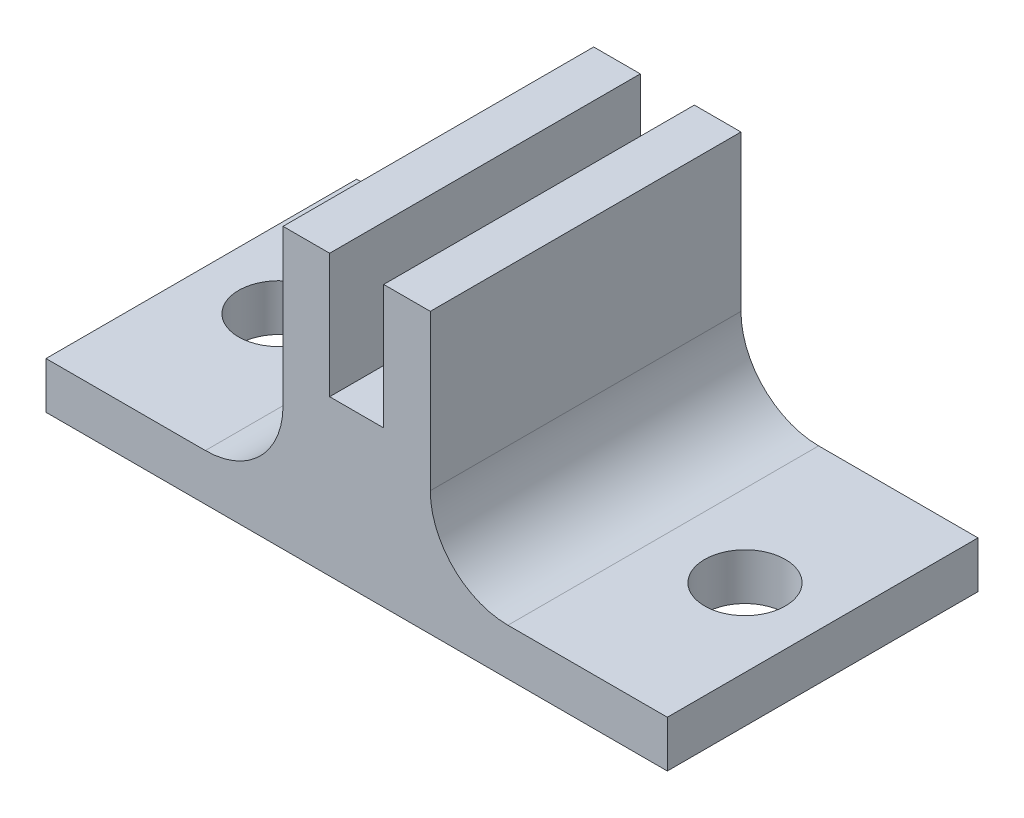
SolidWorks part; units mm, degrees
ref_plane "Front Plane" through (0, 0, 0) normal (0, 0, 1) x (1, 0, 0)
ref_plane "Top Plane" through (0, 0, 0) normal (0, 1, 0) x (1, 0, 0)
ref_plane "Right Plane" through (0, 0, 0) normal (1, 0, 0) x (0, 0, -1)
sketch "Sketch3" plane through (0, 0, 0) normal (0, 1, 0) x (1, 0, 0)
  line L0 (0, 0) -> (0, 20.1744) construction
  line L1 (-20, -10) -> (20, -10)
  line L2 (-20, -10) -> (-20, 10)
  line L3 (-20, 10) -> (20, 10)
  line L4 (20, -10) -> (20, 10)
  line L5 (-20, -10) -> (20, 10) construction
  line L6 (-20, 10) -> (20, -10) construction
  circle A0 centre (-15, 0) radius 2.6
  circle A1 centre (15, 0) radius 2.6
  point P0 (0, 0)
  dimension "D3" = 5.2
  dimension "D4" = 15
  dimension "D1" = 20
  dimension "D2" = 40
extrude "Jig base" add sketch "Sketch3" along normal blind 3
sketch "Sketch4" plane through (0, 3, 0) normal (0, 1, 0) x (1, 0, 0)
  line L5 (-4.74, 10) -> (-1.74, 10)
  line L6 (-1.74, 10) -> (1.74, 10) construction
  line L11 (-4.74, 10) -> (-4.74, -10)
  line L12 (-4.74, -10) -> (-1.74, -10)
  line L13 (-1.74, 10) -> (-1.74, -10)
  line L14 (4.74, -10) -> (1.74, -10)
  line L15 (4.74, -10) -> (4.74, 10)
  line L16 (4.74, 10) -> (1.74, 10)
  line L17 (1.74, -10) -> (1.74, 10)
  line L18 (20, 10) -> (-20, 10) construction
  point P12 (0, 10)
  point P18 (-1.74, 0)
  point P19 (1.74, 0)
  dimension "D1" = 3
  dimension "D2" = 3
  dimension "D3" = 3.48
  dimension "D4" = 20
extrude "jig wall" add sketch "Sketch4" along normal blind 15
sketch "Sketch5" plane through (4.74, 0, 0) normal (1, 0, 0) x (0, 0, -1)
  line L0 (10, 18) -> (10, 3) construction
  line L1 (-10, 0) -> (10, 0)
  line L2 (-10, 0) -> (-10, 10)
  line L3 (-10, 10) -> (-1.55, 10)
  line L4 (10, 0) -> (10, 10)
  line L5 (-1.55, 10) -> (-1.55, 14)
  line L6 (-1.55, 14) -> (1.55, 14)
  line L7 (1.55, 14) -> (1.55, 10)
  line L8 (1.55, 10) -> (10, 10)
  line L9 (-10, 18) -> (-10, 3) construction
  point P9 (0, 14)
  dimension "D1" = 10
  dimension "D2" = 4
  dimension "D3" = 3.1
extrude "stringer lock" add sketch "Sketch5" against normal up to surface (9.48 mm away) up to face at (-4.74, 10.5, 0)
fillet "base filet" radius 5 2 edges at (-4.74, 3, 0) (4.74, 3, 0)
